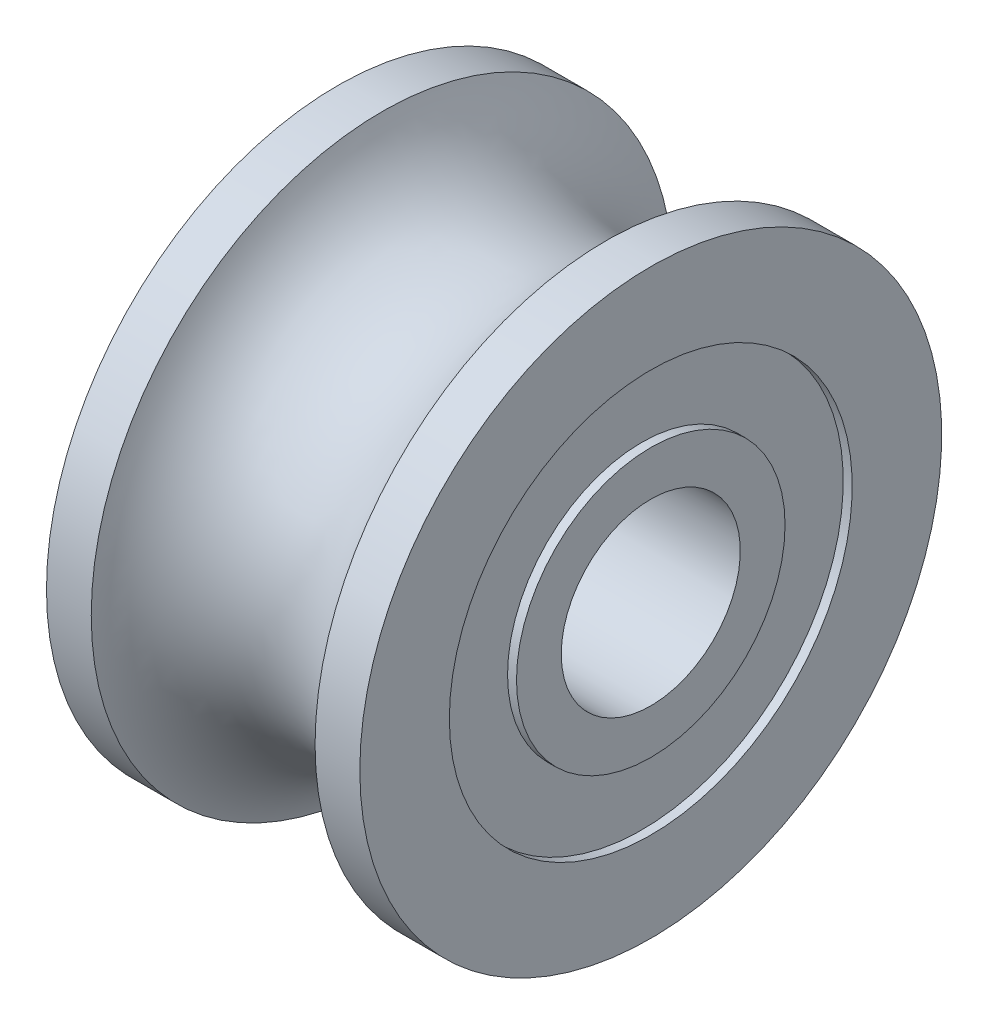
SolidWorks part; units mm, degrees
material "Acier allié"
ref_plane "Plan de face" through (0, 0, 0) normal (0, 0, 1) x (1, 0, 0)
ref_plane "Plan de dessus" through (0, 0, 0) normal (0, 1, 0) x (1, 0, 0)
ref_plane "Plan de droite" through (0, 0, 0) normal (1, 0, 0) x (0, 0, -1)
sketch "Esquisse1" plane through (0, 0, 0) normal (0, 0, 1) x (1, 0, 0)
  line L1 (-3.5, 3) -> (-3.3, 3)
  line L2 (-3.5, 3) -> (-3.5, 2)
  line L3 (-3.5, 2) -> (3.5, 2)
  line L4 (3.5, 3) -> (3.5, 2)
  line L5 (3.3, 4.5) -> (3.5, 4.5)
  line L6 (-3.3, 4.5) -> (-3.3, 3)
  line L8 (3.3, 4.5) -> (3.3, 3)
  line L9 (-3.5, 6.5) -> (-2.5, 6.5)
  line L10 (-3.5, 6.5) -> (-3.5, 4.5)
  line L11 (-3.5, 4.5) -> (-3.3, 4.5)
  line L12 (3.5, 6.5) -> (3.5, 4.5)
  line L14 (2.5, 6.5) -> (3.5, 6.5)
  line L15 (-3.5, 0) -> (3.5, 0) construction
  line L16 (3.3, 3) -> (3.5, 3)
  arc A0 (-2.5, 6.5) -> (2.5, 6.5) centre (0, 7.4107) ccw
  point P18 (0, 2)
  dimension "D9" = 9.5
  dimension "D7" = 7.4107
  dimension "D10" = 2.6607
  dimension "D1" = 13
  dimension "D2" = 7
  dimension "D3" = 4
  dimension "D4" = 6
  dimension "D5" = 9
  dimension "D6" = 0.2
  dimension "D8" = 1
revolve "Révolution1" add sketch "Esquisse1" angle 360 about L15
